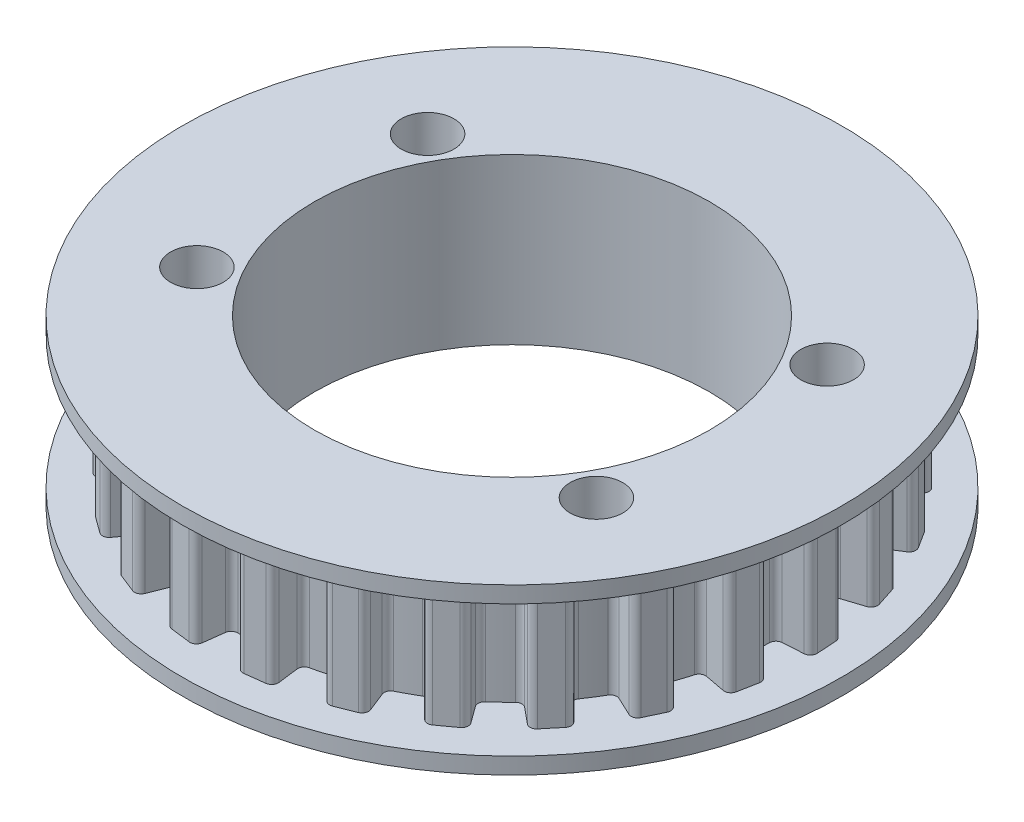
SolidWorks part; units mm, degrees
ref_plane "Alzado" through (0, 0, 0) normal (0, 0, 1) x (1, 0, 0)
ref_plane "Planta" through (0, 0, 0) normal (0, 1, 0) x (1, 0, 0)
ref_plane "Vista lateral" through (0, 0, 0) normal (1, 0, 0) x (0, 0, -1)
sketch "Croquis1" plane through (0, 0, 0) normal (0, 1, 0) x (1, 0, 0)
  line L0 (0, 0) -> (0, 45) construction
  line L1 (-1.5, 45) -> (1.5, 45)
  line L2 (-2.5, 44) -> (-2.5, 40.8503)
  line L3 (2.5, 44) -> (2.5, 40.8503)
  line L4 (9.7382, 43.9593) -> (12.6439, 43.2132)
  line L5 (13.3638, 41.9959) -> (12.5805, 38.9452)
  line L6 (8.5209, 43.2394) -> (7.7376, 40.1887)
  line L7 (20.3645, 40.1564) -> (22.9934, 38.7112)
  line L8 (23.3879, 37.3531) -> (21.8706, 34.593)
  line L9 (19.0064, 39.7619) -> (17.489, 37.0018)
  line L10 (29.7112, 33.8304) -> (31.8981, 31.7768)
  line L11 (31.9425, 30.3633) -> (29.7864, 28.0672)
  line L12 (28.2977, 33.786) -> (26.1416, 31.49)
  line L13 (37.191, 25.3787) -> (38.7985, 22.8457)
  line L14 (38.49, 21.4656) -> (35.8306, 19.7779)
  line L15 (35.8109, 25.6872) -> (33.1515, 23.9995)
  line L16 (42.334, 15.3323) -> (43.2611, 12.4792)
  line L17 (42.619, 11.2191) -> (39.6235, 10.2458)
  line L18 (41.0739, 15.9744) -> (38.0784, 15.0011)
  line L19 (44.817, 4.3226) -> (45.0054, 1.3285)
  line L20 (44.0702, 0.2677) -> (40.9267, 0.0699)
  line L21 (43.7562, 5.2578) -> (40.6128, 5.0601)
  line L22 (44.484, -6.9587) -> (43.9219, -9.9056)
  line L23 (42.7522, -10.7005) -> (39.6583, -10.1103)
  line L24 (43.6891, -5.7891) -> (40.5952, -5.1989)
  line L25 (41.3559, -17.8028) -> (40.0785, -20.5173)
  line L26 (38.7479, -20.9964) -> (35.898, -19.6553)
  line L27 (40.8768, -16.4722) -> (38.0269, -15.1312)
  line L28 (35.6292, -27.5283) -> (33.717, -29.8398)
  line L29 (32.309, -29.9729) -> (29.8822, -27.9653)
  line L30 (35.4961, -26.1204) -> (33.0693, -24.1127)
  line L31 (27.6639, -35.5241) -> (25.2368, -37.2874)
  line L32 (23.84, -37.0662) -> (21.9887, -34.5181)
  line L33 (27.8851, -34.1273) -> (26.0338, -31.5792)
  line L34 (17.9603, -41.2878) -> (15.1709, -42.3921)
  line L35 (13.873, -41.8305) -> (12.7136, -38.902)
  line L36 (18.5219, -39.9899) -> (17.3625, -37.0614)
  line L37 (7.1282, -44.4572) -> (4.1518, -44.8332)
  line L38 (3.0344, -43.9664) -> (2.6396, -40.8416)
  line L39 (7.9949, -43.3397) -> (7.6002, -40.2149)
  line L40 (-4.1518, -44.8332) -> (-7.1282, -44.4572)
  line L41 (-7.9949, -43.3397) -> (-7.6002, -40.2149)
  line L42 (-3.0344, -43.9664) -> (-2.6396, -40.8416)
  line L43 (-15.1709, -42.3921) -> (-17.9603, -41.2878)
  line L44 (-18.5219, -39.9899) -> (-17.3625, -37.0614)
  line L45 (-13.873, -41.8305) -> (-12.7136, -38.902)
  line L46 (-25.2368, -37.2874) -> (-27.6639, -35.5241)
  line L47 (-27.8851, -34.1273) -> (-26.0338, -31.5792)
  line L48 (-23.84, -37.0662) -> (-21.9887, -34.5181)
  line L49 (-33.717, -29.8398) -> (-35.6292, -27.5283)
  line L50 (-35.4961, -26.1204) -> (-33.0693, -24.1127)
  line L51 (-32.309, -29.9729) -> (-29.8822, -27.9653)
  line L52 (-40.0785, -20.5173) -> (-41.3559, -17.8028)
  line L53 (-40.8768, -16.4722) -> (-38.0269, -15.1312)
  line L54 (-38.7479, -20.9964) -> (-35.898, -19.6553)
  line L55 (-43.9219, -9.9056) -> (-44.484, -6.9587)
  line L56 (-43.6891, -5.7891) -> (-40.5952, -5.1989)
  line L57 (-42.7522, -10.7005) -> (-39.6583, -10.1103)
  line L58 (-45.0054, 1.3285) -> (-44.817, 4.3226)
  line L59 (-43.7562, 5.2578) -> (-40.6128, 5.0601)
  line L60 (-44.0702, 0.2677) -> (-40.9267, 0.0699)
  line L61 (-43.2611, 12.4792) -> (-42.334, 15.3323)
  line L62 (-41.0739, 15.9744) -> (-38.0784, 15.0011)
  line L63 (-42.619, 11.2191) -> (-39.6235, 10.2458)
  line L64 (-38.7985, 22.8457) -> (-37.191, 25.3787)
  line L65 (-35.8109, 25.6872) -> (-33.1515, 23.9995)
  line L66 (-38.49, 21.4656) -> (-35.8306, 19.7779)
  line L67 (-31.8981, 31.7768) -> (-29.7112, 33.8304)
  line L68 (-28.2977, 33.786) -> (-26.1416, 31.49)
  line L69 (-31.9425, 30.3633) -> (-29.7864, 28.0672)
  line L70 (-22.9934, 38.7112) -> (-20.3645, 40.1564)
  line L71 (-19.0064, 39.7619) -> (-17.489, 37.0018)
  line L72 (-23.3879, 37.3531) -> (-21.8706, 34.593)
  line L73 (-12.6439, 43.2132) -> (-9.7382, 43.9593)
  line L74 (-8.5209, 43.2394) -> (-7.7376, 40.1887)
  line L75 (-13.3638, 41.9959) -> (-12.5805, 38.9452)
  circle A0 centre (0, 0) radius 30
  arc A1 (-3.4146, 39.854) -> (-6.6039, 39.4511) centre (0, 0) ccw
  circle A2 centre (0, 0) radius 45 construction
  arc A4 (-2.5, 44) -> (-1.5, 45) centre (-1.5, 44) cw
  arc A5 (2.5, 44) -> (1.5, 45) centre (1.5, 44) ccw
  arc A6 (3.4146, 39.854) -> (2.5, 40.8503) centre (3.5, 40.8503) cw
  arc A7 (-3.4146, 39.854) -> (-2.5, 40.8503) centre (-3.5, 40.8503) ccw
  arc A8 (8.5209, 43.2394) -> (9.7382, 43.9593) centre (9.4895, 42.9907) cw
  arc A9 (13.3638, 41.9959) -> (12.6439, 43.2132) centre (12.3952, 42.2446) ccw
  arc A10 (13.2186, 37.7527) -> (12.5805, 38.9452) centre (13.5491, 38.6965) cw
  arc A11 (6.6039, 39.4511) -> (7.7376, 40.1887) centre (6.769, 40.4374) ccw
  arc A12 (19.0064, 39.7619) -> (20.3645, 40.1564) centre (19.8827, 39.2801) cw
  arc A13 (23.3879, 37.3531) -> (22.9934, 38.7112) centre (22.5116, 37.8349) ccw
  arc A14 (22.1921, 33.2793) -> (21.8706, 34.593) centre (22.7469, 34.1113) cw
  arc A15 (16.2075, 36.5693) -> (17.489, 37.0018) centre (16.6127, 37.4836) ccw
  arc A16 (28.2977, 33.786) -> (29.7112, 33.8304) centre (29.0266, 33.1014) cw
  arc A17 (31.9425, 30.3633) -> (31.8981, 31.7768) centre (31.2135, 31.0478) ccw
  arc A18 (29.7711, 26.7148) -> (29.7864, 28.0672) centre (30.5154, 27.3827) cw
  arc A19 (24.7928, 31.3898) -> (26.1416, 31.49) centre (25.4126, 32.1745) ccw
  arc A20 (35.8109, 25.6872) -> (37.191, 25.3787) centre (36.3467, 24.8429) cw
  arc A21 (38.49, 21.4656) -> (38.7985, 22.8457) centre (37.9542, 22.3099) ccw
  arc A22 (35.4795, 18.4718) -> (35.8306, 19.7779) centre (36.3665, 18.9336) cw
  arc A23 (31.8202, 24.2379) -> (33.1515, 23.9995) centre (32.6157, 24.8439) ccw
  arc A24 (41.0739, 15.9744) -> (42.334, 15.3323) centre (41.383, 15.0233) cw
  arc A25 (42.619, 11.2191) -> (43.2611, 12.4792) centre (42.31, 12.1702) ccw
  arc A26 (38.9586, 9.068) -> (39.6235, 10.2458) centre (39.9325, 9.2948) cw
  arc A27 (36.8482, 15.5631) -> (38.0784, 15.0011) centre (37.7694, 15.9521) ccw
  arc A28 (43.7562, 5.2578) -> (44.817, 4.3226) centre (43.819, 4.2598) cw
  arc A29 (44.0702, 0.2677) -> (45.0054, 1.3285) centre (44.0074, 1.2657) ccw
  arc A30 (39.9898, -0.9054) -> (40.9267, 0.0699) centre (40.9895, -0.9281) cw
  arc A31 (39.5609, 5.9103) -> (40.6128, 5.0601) centre (40.55, 6.0581) ccw
  arc A32 (43.6891, -5.7891) -> (44.484, -6.9587) centre (43.5017, -6.7713) cw
  arc A33 (42.7522, -10.7005) -> (43.9219, -9.9056) centre (42.9396, -9.7182) ccw
  arc A34 (38.5082, -10.822) -> (39.6583, -10.1103) centre (39.4709, -11.0926) cw
  arc A35 (39.7879, -4.1137) -> (40.5952, -5.1989) centre (40.7826, -4.2166) ccw
  arc A36 (40.8768, -16.4722) -> (41.3559, -17.8028) centre (40.4511, -17.377) cw
  arc A37 (38.7479, -20.9964) -> (40.0785, -20.5173) centre (39.1737, -20.0915) ccw
  arc A38 (34.6071, -20.0587) -> (35.898, -19.6553) centre (35.4723, -20.5601) cw
  arc A39 (37.5148, -13.8793) -> (38.0269, -15.1312) centre (38.4527, -14.2263) ccw
  arc A40 (35.4961, -26.1204) -> (35.6292, -27.5283) centre (34.8587, -26.8909) cw
  arc A41 (32.309, -29.9729) -> (33.717, -29.8398) centre (32.9464, -29.2024) ccw
  arc A42 (28.5315, -28.0349) -> (29.8822, -27.9653) centre (29.2447, -28.7358) cw
  arc A43 (32.8846, -22.7729) -> (33.0693, -24.1127) centre (33.7067, -23.3422) ccw
  arc A44 (27.8851, -34.1273) -> (27.6639, -35.5241) centre (27.0761, -34.7151) cw
  arc A45 (23.84, -37.0662) -> (25.2368, -37.2874) centre (24.649, -36.4784) ccw
  arc A46 (20.6631, -34.2496) -> (21.9887, -34.5181) centre (21.1797, -35.1059) cw
  arc A47 (26.1881, -30.2355) -> (26.0338, -31.5792) centre (26.8428, -30.9914) ccw
  arc A48 (18.5219, -39.9899) -> (17.9603, -41.2878) centre (17.5921, -40.358) cw
  arc A49 (13.873, -41.8305) -> (15.1709, -42.3921) centre (14.8028, -41.4624) ccw
  arc A50 (11.4964, -38.3123) -> (12.7136, -38.902) centre (11.7838, -39.2701) cw
  arc A51 (17.8461, -35.7983) -> (17.3625, -37.0614) centre (18.2922, -36.6932) ccw
  arc A52 (7.9949, -43.3397) -> (7.1282, -44.4572) centre (7.0028, -43.465) cw
  arc A53 (3.0344, -43.9664) -> (4.1518, -44.8332) centre (4.0265, -43.841) ccw
  arc A54 (1.6073, -39.9677) -> (2.6396, -40.8416) centre (1.6475, -40.9669) cw
  arc A55 (8.3827, -39.1118) -> (7.6002, -40.2149) centre (8.5923, -40.0896) ccw
  arc A56 (-3.0344, -43.9664) -> (-4.1518, -44.8332) centre (-4.0265, -43.841) cw
  arc A57 (-7.9949, -43.3397) -> (-7.1282, -44.4572) centre (-7.0028, -43.465) ccw
  arc A58 (-8.3827, -39.1118) -> (-7.6002, -40.2149) centre (-8.5923, -40.0896) cw
  arc A59 (-1.6073, -39.9677) -> (-2.6396, -40.8416) centre (-1.6475, -40.9669) ccw
  arc A60 (-13.873, -41.8305) -> (-15.1709, -42.3921) centre (-14.8028, -41.4624) cw
  arc A61 (-18.5219, -39.9899) -> (-17.9603, -41.2878) centre (-17.5921, -40.358) ccw
  arc A62 (-17.8461, -35.7983) -> (-17.3625, -37.0614) centre (-18.2922, -36.6932) cw
  arc A63 (-11.4964, -38.3123) -> (-12.7136, -38.902) centre (-11.7838, -39.2701) ccw
  arc A64 (-23.84, -37.0662) -> (-25.2368, -37.2874) centre (-24.649, -36.4784) cw
  arc A65 (-27.8851, -34.1273) -> (-27.6639, -35.5241) centre (-27.0761, -34.7151) ccw
  arc A66 (-26.1881, -30.2355) -> (-26.0338, -31.5792) centre (-26.8428, -30.9914) cw
  arc A67 (-20.6631, -34.2496) -> (-21.9887, -34.5181) centre (-21.1797, -35.1059) ccw
  arc A68 (-32.309, -29.9729) -> (-33.717, -29.8398) centre (-32.9464, -29.2024) cw
  arc A69 (-35.4961, -26.1204) -> (-35.6292, -27.5283) centre (-34.8587, -26.8909) ccw
  arc A70 (-32.8846, -22.7729) -> (-33.0693, -24.1127) centre (-33.7067, -23.3422) cw
  arc A71 (-28.5315, -28.0349) -> (-29.8822, -27.9653) centre (-29.2447, -28.7358) ccw
  arc A72 (-38.7479, -20.9964) -> (-40.0785, -20.5173) centre (-39.1737, -20.0915) cw
  arc A73 (-40.8768, -16.4722) -> (-41.3559, -17.8028) centre (-40.4511, -17.377) ccw
  arc A74 (-37.5148, -13.8793) -> (-38.0269, -15.1312) centre (-38.4527, -14.2263) cw
  arc A75 (-34.6071, -20.0587) -> (-35.898, -19.6553) centre (-35.4723, -20.5601) ccw
  arc A76 (-42.7522, -10.7005) -> (-43.9219, -9.9056) centre (-42.9396, -9.7182) cw
  arc A77 (-43.6891, -5.7891) -> (-44.484, -6.9587) centre (-43.5017, -6.7713) ccw
  arc A78 (-39.7879, -4.1137) -> (-40.5952, -5.1989) centre (-40.7826, -4.2166) cw
  arc A79 (-38.5082, -10.822) -> (-39.6583, -10.1103) centre (-39.4709, -11.0926) ccw
  arc A80 (-44.0702, 0.2677) -> (-45.0054, 1.3285) centre (-44.0074, 1.2657) cw
  arc A81 (-43.7562, 5.2578) -> (-44.817, 4.3226) centre (-43.819, 4.2598) ccw
  arc A82 (-39.5609, 5.9103) -> (-40.6128, 5.0601) centre (-40.55, 6.0581) cw
  arc A83 (-39.9898, -0.9054) -> (-40.9267, 0.0699) centre (-40.9895, -0.9281) ccw
  arc A84 (-42.619, 11.2191) -> (-43.2611, 12.4792) centre (-42.31, 12.1702) cw
  arc A85 (-41.0739, 15.9744) -> (-42.334, 15.3323) centre (-41.383, 15.0233) ccw
  arc A86 (-36.8482, 15.5631) -> (-38.0784, 15.0011) centre (-37.7694, 15.9521) cw
  arc A87 (-38.9586, 9.068) -> (-39.6235, 10.2458) centre (-39.9325, 9.2948) ccw
  arc A88 (-38.49, 21.4656) -> (-38.7985, 22.8457) centre (-37.9542, 22.3099) cw
  arc A89 (-35.8109, 25.6872) -> (-37.191, 25.3787) centre (-36.3467, 24.8429) ccw
  arc A90 (-31.8202, 24.2379) -> (-33.1515, 23.9995) centre (-32.6157, 24.8439) cw
  arc A91 (-35.4795, 18.4718) -> (-35.8306, 19.7779) centre (-36.3665, 18.9336) ccw
  arc A92 (-31.9425, 30.3633) -> (-31.8981, 31.7768) centre (-31.2135, 31.0478) cw
  arc A93 (-28.2977, 33.786) -> (-29.7112, 33.8304) centre (-29.0266, 33.1014) ccw
  arc A94 (-24.7928, 31.3898) -> (-26.1416, 31.49) centre (-25.4126, 32.1745) cw
  arc A95 (-29.7711, 26.7148) -> (-29.7864, 28.0672) centre (-30.5154, 27.3827) ccw
  arc A96 (-23.3879, 37.3531) -> (-22.9934, 38.7112) centre (-22.5116, 37.8349) cw
  arc A97 (-19.0064, 39.7619) -> (-20.3645, 40.1564) centre (-19.8827, 39.2801) ccw
  arc A98 (-16.2075, 36.5693) -> (-17.489, 37.0018) centre (-16.6127, 37.4836) cw
  arc A99 (-22.1921, 33.2793) -> (-21.8706, 34.593) centre (-22.7469, 34.1113) ccw
  arc A100 (-13.3638, 41.9959) -> (-12.6439, 43.2132) centre (-12.3952, 42.2446) cw
  arc A101 (-8.5209, 43.2394) -> (-9.7382, 43.9593) centre (-9.4895, 42.9907) ccw
  arc A102 (-6.6039, 39.4511) -> (-7.7376, 40.1887) centre (-6.769, 40.4374) cw
  arc A103 (-13.2186, 37.7527) -> (-12.5805, 38.9452) centre (-13.5491, 38.6965) ccw
  arc A104 (6.6039, 39.4511) -> (3.4146, 39.854) centre (0, 0) ccw
  arc A105 (16.2075, 36.5693) -> (13.2186, 37.7527) centre (0, 0) ccw
  arc A106 (24.7928, 31.3898) -> (22.1921, 33.2793) centre (0, 0) ccw
  arc A107 (31.8202, 24.2379) -> (29.7711, 26.7148) centre (0, 0) ccw
  arc A108 (36.8482, 15.5631) -> (35.4795, 18.4718) centre (0, 0) ccw
  arc A109 (39.5609, 5.9103) -> (38.9586, 9.068) centre (0, 0) ccw
  arc A110 (39.7879, -4.1137) -> (39.9898, -0.9054) centre (0, 0) ccw
  arc A111 (37.5148, -13.8793) -> (38.5082, -10.822) centre (0, 0) ccw
  arc A112 (32.8846, -22.7729) -> (34.6071, -20.0587) centre (0, 0) ccw
  arc A113 (26.1881, -30.2355) -> (28.5315, -28.0349) centre (0, 0) ccw
  arc A114 (17.8461, -35.7983) -> (20.6631, -34.2496) centre (0, 0) ccw
  arc A115 (8.3827, -39.1118) -> (11.4964, -38.3123) centre (0, 0) ccw
  arc A116 (-1.6073, -39.9677) -> (1.6073, -39.9677) centre (0, 0) ccw
  arc A117 (-11.4964, -38.3123) -> (-8.3827, -39.1118) centre (0, 0) ccw
  arc A118 (-20.6631, -34.2496) -> (-17.8461, -35.7983) centre (0, 0) ccw
  arc A119 (-28.5315, -28.0349) -> (-26.1881, -30.2355) centre (0, 0) ccw
  arc A120 (-34.6071, -20.0587) -> (-32.8846, -22.7729) centre (0, 0) ccw
  arc A121 (-38.5082, -10.822) -> (-37.5148, -13.8793) centre (0, 0) ccw
  arc A122 (-39.9898, -0.9054) -> (-39.7879, -4.1137) centre (0, 0) ccw
  arc A123 (-38.9586, 9.068) -> (-39.5609, 5.9103) centre (0, 0) ccw
  arc A124 (-35.4795, 18.4718) -> (-36.8482, 15.5631) centre (0, 0) ccw
  arc A125 (-29.7711, 26.7148) -> (-31.8202, 24.2379) centre (0, 0) ccw
  arc A126 (-22.1921, 33.2793) -> (-24.7928, 31.3898) centre (0, 0) ccw
  arc A127 (-13.2186, 37.7527) -> (-16.2075, 36.5693) centre (0, 0) ccw
  point P9 (0, 45)
  point P10 (0, 45)
  point P13 (-2.5, 45)
  point P16 (2.5, 45)
  point P312 (0, 0)
  dimension "D1" = 80
  dimension "D2" = 60
  dimension "D3" = 90
  dimension "D4" = 5
  dimension "D5" = 1
  dimension "D6" = 25
extrude "Saliente-Extruir1" add sketch "Croquis1" along normal mid plane 20
sketch "Croquis2" plane through (0, 10, 0) normal (0, 1, 0) x (1, 0, 0)
  circle A0 centre (0, 0) radius 50
  dimension "D1" = 100
extrude "Saliente-Extruir2" add sketch "Croquis2" along normal blind 2.5
sketch "Croquis3" plane through (0, -10, 0) normal (0, -1, 0) x (1, 0, 0)
  circle A0 centre (0, 0) radius 50
  dimension "D1" = 100
extrude "Saliente-Extruir3" add sketch "Croquis3" along normal blind 2.5
sketch "Croquis4" plane through (0, 0, 0) normal (0, 1, 0) x (1, 0, 0)
  circle A0 centre (0, 0) radius 30
  dimension "D1" = 60
extrude "Cortar-Extruir1" cut sketch "Croquis4" against normal mid plane 25
sketch "Croquis6" plane through (0, 12.5, 0) normal (0, 1, 0) x (1, 0, 0)
  line L0 (0, 0) -> (35, 0) construction
  line L1 (0, 0) -> (30.3109, 17.5) construction
  line L2 (0, 0) -> (0, 30) construction
  circle A0 centre (0, 0) radius 35 construction
  circle A1 centre (30.3109, 17.5) radius 4
  circle A2 centre (30.3109, -17.5) radius 4
  circle A3 centre (0, 0) radius 30 construction
  circle A4 centre (-30.3109, -17.5) radius 4
  circle A5 centre (-30.3109, 17.5) radius 4
  dimension "D1" = 70
  dimension "D3" = 8
  dimension "D2" = 30
extrude "Cortar-Extruir2" cut sketch "Croquis6" against normal blind 10
